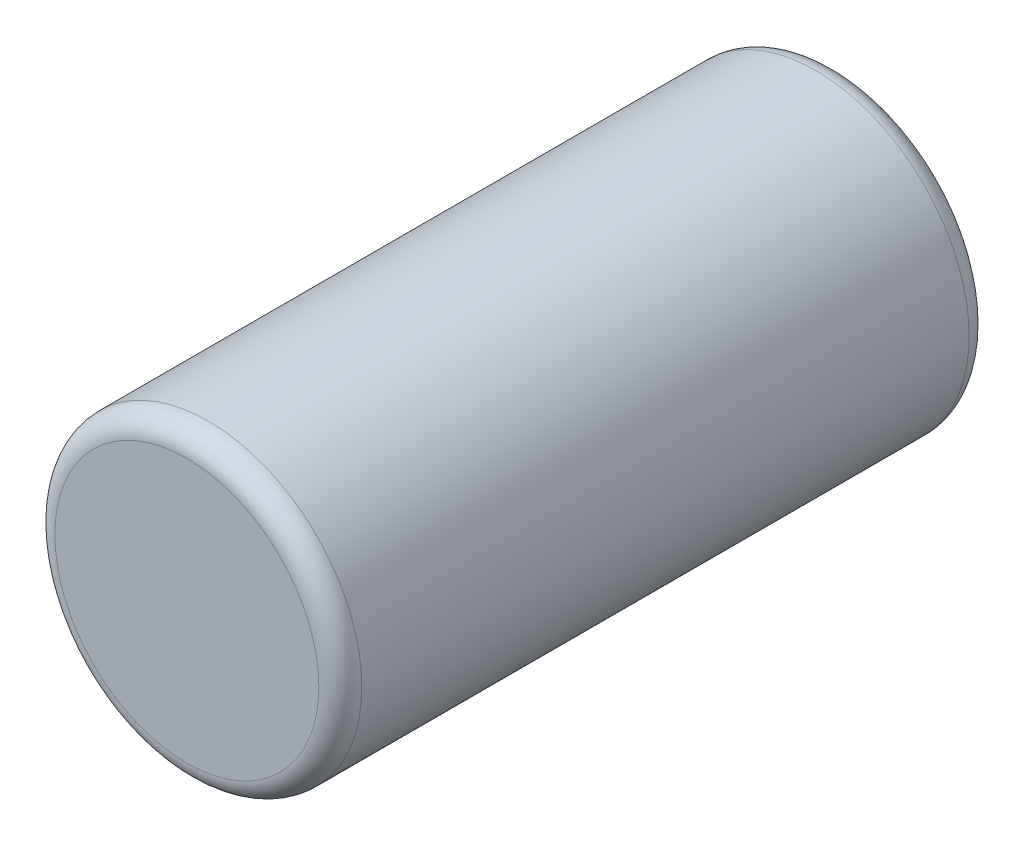
SolidWorks part; units mm, degrees
material "17CrNiMo6"
ref_plane "Front Plane" through (0, 0, 0) normal (0, 0, 1) x (1, 0, 0)
ref_plane "Top Plane" through (0, 0, 0) normal (0, 1, 0) x (1, 0, 0)
ref_plane "Right Plane" through (0, 0, 0) normal (1, 0, 0) x (0, 0, -1)
sketch "Sketch1" plane through (0, 0, 0) normal (1, 0, 0) x (0, 0, -1)
  line L0 (0, 0) -> (68.053, 0) construction
  line L1 (0, 0) -> (0, 6.15)
  line L2 (1, 7.15) -> (29.3, 7.15)
  line L3 (30.3, 6.15) -> (30.3, 0)
  line L4 (0, 0) -> (30.3, 0)
  arc A0 (29.3, 7.15) -> (30.3, 6.15) centre (29.3, 6.15) cw
  arc A1 (0, 6.15) -> (1, 7.15) centre (1, 6.15) cw
  dimension "D3" = 1
  dimension "D1" = 14.3
  dimension "D2" = 30.3
revolve "Revolve1" add sketch "Sketch1" angle 360 about L0
